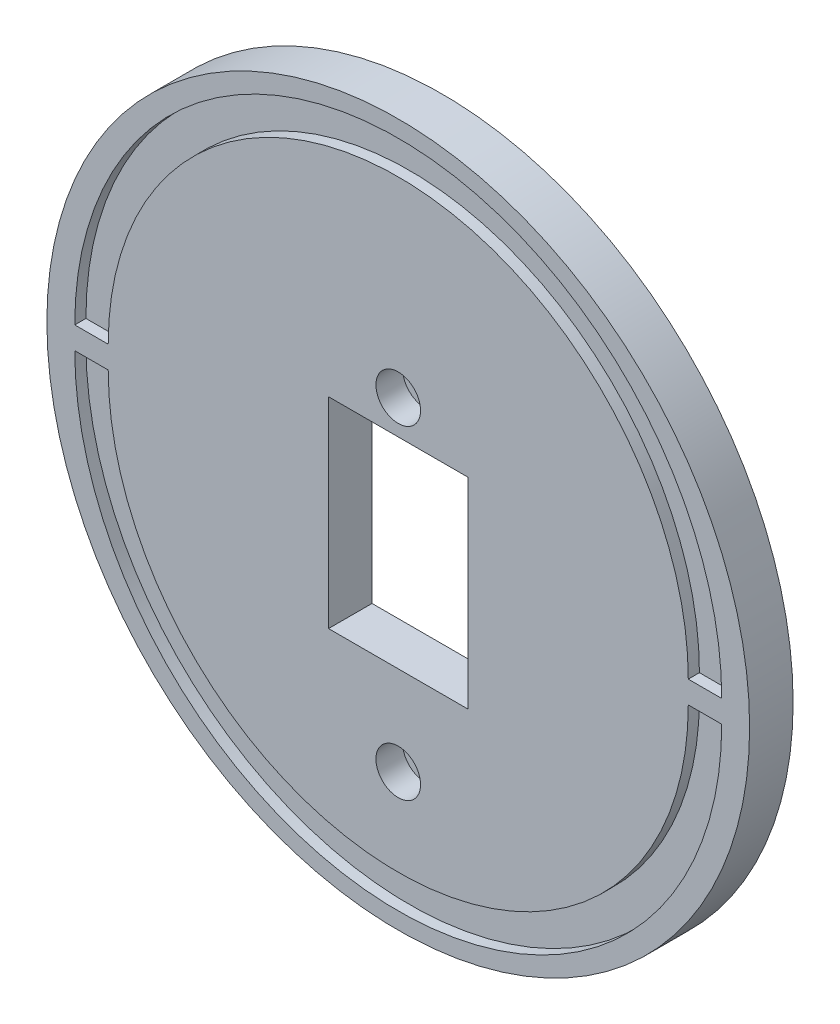
SolidWorks part; units mm, degrees
ref_plane "Alzado" through (0, 0, 0) normal (0, 0, 1) x (1, 0, 0)
ref_plane "Planta" through (0, 0, 0) normal (0, 1, 0) x (1, 0, 0)
ref_plane "Vista lateral" through (0, 0, 0) normal (1, 0, 0) x (0, 0, -1)
sketch "Croquis1" plane through (0, 0, 0) normal (0, 0, 1) x (1, 0, 0)
  circle A0 centre (-51.2357, 9.7866) radius 31.5
  dimension "D1" = 63
extrude "Saliente-Extruir1" add sketch "Croquis1" along normal blind 2.4
sketch "Croquis2" plane through (0, 0, 2.4) normal (0, 0, 1) x (1, 0, 0)
  line L0 (-51.2357, 9.7866) -> (-51.2357, -21.7134) construction
  line L1 (-51.2357, 9.7866) -> (-51.2357, 14.7866) construction
  line L2 (-51.2357, 14.7866) -> (-51.2357, 19.7866) construction
  line L3 (-51.2357, 19.7866) -> (-51.2357, 21.5866) construction
  line L4 (-51.2357, 21.5866) -> (-57.4857, 21.5866) construction
  line L6 (-57.4857, 21.5866) -> (-44.9857, 21.5866)
  line L7 (-57.4857, 21.5866) -> (-57.4857, -11.4134)
  line L8 (-57.4857, -11.4134) -> (-44.9857, -11.4134)
  line L9 (-44.9857, 21.5866) -> (-44.9857, -11.4134)
  line L14 (-59.2857, 23.3866) -> (-43.1857, 23.3866)
  line L15 (-59.2857, 23.3866) -> (-59.2857, -13.2134)
  line L16 (-59.2857, -13.2134) -> (-43.1857, -13.2134)
  line L17 (-43.1857, 23.3866) -> (-43.1857, -13.2134)
  circle A0 centre (-51.2357, 9.7866) radius 31.5 construction
  dimension "D2" = 5
  dimension "D3" = 1.8
  dimension "D4" = 6.25
  dimension "D5" = 12.5
  dimension "D6" = 33
  dimension "D7" = 1.8
  dimension "D8" = 1.8
  dimension "D9" = 1.8
  dimension "D10" = 1.8
  dimension "D11" = 8.5
extrude "Saliente-Extruir2" add sketch "Croquis2" along normal blind 22.5
sketch "Croquis5" plane through (0, 0, 2.4) normal (0, 0, 1) x (1, 0, 0)
  line L1 (-59.2857, 23.3866) -> (-43.1857, 23.3866)
  line L2 (-59.2857, 23.3866) -> (-59.2857, -13.2134)
  line L3 (-59.2857, -13.2134) -> (-43.1857, -13.2134)
  line L4 (-43.1857, 23.3866) -> (-43.1857, -13.2134)
extrude "Cortar-Extruir2" cut sketch "Croquis5" against normal blind 9
sketch "Croquis6" plane through (0, 0, 0) normal (0, 0, -1) x (-1, 0, 0)
  line L6 (51.2357, 9.7866) -> (73.5095, 32.0605) construction
  line L7 (73.5095, 32.0605) -> (73.5095, -12.4873) construction
  line L8 (73.5095, -12.4873) -> (28.9618, 32.0605) construction
  line L9 (28.9618, 32.0605) -> (28.9618, -12.4873) construction
  line L10 (28.9618, -12.4873) -> (51.2357, 9.7866) construction
  line L11 (51.2357, 23.3866) -> (53.2357, 23.3866)
  line L12 (43.1857, 23.3866) -> (59.2857, 23.3866) construction
  line L13 (53.2357, 23.3866) -> (53.2357, 43.3866)
  line L14 (53.2357, 43.3866) -> (49.2357, 43.3866)
  line L15 (49.2357, 43.3866) -> (49.2357, 23.3866)
  line L16 (49.2357, 23.3866) -> (51.2357, 23.3866)
  circle A0 centre (51.2357, 9.7866) radius 31.5 construction
  circle A1 centre (34.6187, 26.4036) radius 1.5
  circle A2 centre (67.8527, 26.4036) radius 1.5
  circle A3 centre (67.8527, -6.8304) radius 1.5
  circle A4 centre (34.6187, -6.8304) radius 1.5
  dimension "D3" = 8
  dimension "D1" = 20
  dimension "D2" = 4
extrude "Cortar-Extruir3" cut sketch "Croquis6" against normal blind 2.4
sketch "Croquis7" plane through (0, 21.5866, 0) normal (0, -1, 0) x (1, 0, 0)
  line L0 (-57.4857, 24.9) -> (-57.4857, 2.4) construction
  line L1 (-57.4857, 17.9) -> (-44.9857, 17.9)
  line L2 (-57.4857, 17.9) -> (-57.4857, 8.9)
  line L3 (-57.4857, 8.9) -> (-44.9857, 8.9)
  line L4 (-44.9857, 17.9) -> (-44.9857, 8.9)
  line L5 (-44.9857, 24.9) -> (-44.9857, 2.4) construction
  line L6 (-44.9857, 24.9) -> (-57.4857, 24.9) construction
  dimension "D1" = 9
  dimension "D2" = 7
extrude "Saliente-Extruir3" add sketch "Croquis7" along normal up to vertex (33 mm away)
sketch "Croquis8" plane through (0, 0, 17.9) normal (0, 0, 1) x (1, 0, 0)
  line L0 (-44.9857, -11.4134) -> (-44.9857, 21.5866) construction
  line L1 (-44.9857, -6.4134) -> (-57.4857, -6.4134)
  line L2 (-44.9857, -6.4134) -> (-44.9857, 16.5866)
  line L4 (-57.4857, -6.4134) -> (-57.4857, 16.5866)
  line L5 (-57.4857, -11.4134) -> (-57.4857, 21.5866) construction
  line L6 (-44.9857, -11.4134) -> (-57.4857, -11.4134) construction
  line L9 (-44.9857, 16.5866) -> (-49.2357, 16.5866)
  line L10 (-49.2357, 16.5866) -> (-49.2357, 18.5866)
  line L11 (-49.2357, 18.5866) -> (-53.2357, 18.5866)
  line L12 (-53.2357, 18.5866) -> (-53.2357, 16.5866)
  line L13 (-53.2357, 16.5866) -> (-57.4857, 16.5866)
  line L14 (-44.9857, 21.5866) -> (-57.4857, 21.5866) construction
  circle A0 centre (-51.2357, -9.4134) radius 1
  circle A1 centre (-51.2357, 19.6366) radius 1
  dimension "D3" = 2
  dimension "D6" = 1.95
  dimension "D1" = 5
  dimension "D2" = 5
  dimension "D4" = 4
  dimension "D5" = 2
  dimension "D7" = 2
extrude "Cortar-Extruir5" cut sketch "Croquis8" against normal blind 9
sketch "Croquis9" plane through (-44.9857, 0, 0) normal (-1, 0, 0) x (0, 0, 1)
  line L0 (8.9, -6.4134) -> (3.9, -11.4134)
  line L1 (8.9, -11.4134) -> (2.4, -11.4134) construction
  line L2 (3.9, -11.4134) -> (8.9, -11.4134)
  line L3 (8.9, -11.4134) -> (8.9, -6.4134)
  line L4 (8.9, 16.5866) -> (3.9, 21.5866)
  line L5 (8.9, 21.5866) -> (2.4, 21.5866) construction
  line L6 (3.9, 21.5866) -> (8.9, 21.5866)
  line L7 (8.9, 21.5866) -> (8.9, 16.5866)
extrude "Saliente-Extruir4" add sketch "Croquis9" along normal up to vertex (12.5 mm away)
sketch "Croquis10" plane through (0, 0, 8.9) normal (0, 0, 1) x (1, 0, 0)
  line L1 (-53.2357, 16.5866) -> (-49.2357, 16.5866)
  line L2 (-53.2357, 16.5866) -> (-53.2357, 18.5866)
  line L3 (-53.2357, 18.5866) -> (-49.2357, 18.5866)
  line L4 (-49.2357, 16.5866) -> (-49.2357, 18.5866)
extrude "Cortar-Extruir6" cut sketch "Croquis10" against normal blind 9
sketch "Croquis11" plane through (0, 0, 24.9) normal (0, 0, 1) x (1, 0, 0)
  line L0 (-57.4857, -11.4134) -> (-44.9857, -11.4134) construction
  line L1 (-57.4857, 16.5866) -> (-44.9857, 16.5866)
  line L2 (-57.4857, 16.5866) -> (-57.4857, -1.4134)
  line L3 (-57.4857, -1.4134) -> (-44.9857, -1.4134)
  line L4 (-44.9857, 16.5866) -> (-44.9857, -1.4134)
  line L5 (-44.9857, 21.5866) -> (-57.4857, 21.5866) construction
  line L6 (-43.1857, -13.2134) -> (-43.1857, 23.3866) construction
  line L7 (-59.2857, 23.3866) -> (-59.2857, -13.2134) construction
  circle A0 centre (-51.2357, 9.7866) radius 31.5
  dimension "D1" = 10
  dimension "D5" = 63
  dimension "D2" = 5
  dimension "D3" = 1.8
  dimension "D4" = 1.8
extrude "Saliente-Extruir5" add sketch "Croquis11" along normal blind 3.9
sketch "Croquis12" plane through (0, 0, 17.9) normal (0, 0, 1) x (1, 0, 0)
  circle A0 centre (-51.2357, 19.6366) radius 1
  circle A1 centre (-51.2357, -9.4134) radius 1
extrude "Cortar-Extruir7" cut sketch "Croquis12" along normal up to vertex
sketch "Croquis13" plane through (0, 0, 28.8) normal (0, 0, 1) x (1, 0, 0)
  circle A0 centre (-51.2357, 19.6366) radius 2
  circle A2 centre (-51.2357, -9.4134) radius 2
extrude "Cortar-Extruir8" cut sketch "Croquis13" against normal blind 2.4
sketch "Croquis14" plane through (0, 0, 0) normal (0, 0, -1) x (-1, 0, 0)
  circle A0 centre (51.2357, 9.7866) radius 31.5
extrude "Cortar-Extruir9" cut sketch "Croquis14" against normal up to vertex (24.9 mm away)
sketch "Croquis15" plane through (0, 0, 28.8) normal (0, 0, 1) x (1, 0, 0)
  line L1 (-44.9857, -1.4134) -> (-57.4857, -1.4134)
  line L2 (-44.9857, -1.4134) -> (-44.9857, 16.5866)
  line L3 (-44.9857, 16.5866) -> (-57.4857, 16.5866)
  line L4 (-57.4857, -1.4134) -> (-57.4857, 16.5866)
  circle A0 centre (-51.2357, 9.7866) radius 31.5
  circle A2 centre (-51.2357, 19.6366) radius 2
  circle A3 centre (-51.2357, -9.4134) radius 2
extrude "Saliente-Extruir6" add sketch "Croquis15" along normal blind 1
sketch "Croquis16" plane through (0, 0, 29.8) normal (0, 0, 1) x (1, 0, 0)
  line L0 (-19.7357, 9.7866) -> (-22.2357, 9.7866) construction
  line L1 (-22.2357, 9.7866) -> (-22.2357, 8.7866) construction
  line L2 (-22.2357, 8.7866) -> (-25.2357, 8.7866)
  line L3 (-51.2357, -1.4134) -> (-51.2357, 16.5866) construction
  line L4 (-57.4857, -1.4134) -> (-44.9857, -1.4134) construction
  line L5 (-44.9857, 16.5866) -> (-57.4857, 16.5866) construction
  line L6 (-22.2357, 9.7866) -> (-22.2357, 10.7866) construction
  line L7 (-22.2357, 10.7866) -> (-25.2357, 10.7866)
  line L8 (-80.2357, 9.7866) -> (-80.2357, 10.7866) construction
  line L9 (-80.2357, 9.7866) -> (-80.2357, 8.7866) construction
  line L10 (-82.7357, 9.7866) -> (-80.2357, 9.7866) construction
  line L11 (-80.2357, 10.7866) -> (-77.2357, 10.7866)
  line L12 (-80.2357, 8.7866) -> (-77.2357, 8.7866)
  circle A0 centre (-51.2357, 9.7866) radius 31.5 construction
  arc A1 (-25.2357, 8.7866) -> (-77.2357, 8.7866) centre (-51.2357, 8.7866) cw
  arc A2 (-22.2357, 8.7866) -> (-80.2357, 8.7866) centre (-51.2357, 8.7866) cw
  arc A3 (-22.2357, 10.7866) -> (-80.2357, 10.7866) centre (-51.2357, 10.7866) ccw
  arc A4 (-25.2357, 10.7866) -> (-77.2357, 10.7866) centre (-51.2357, 10.7866) ccw
  dimension "D1" = 2.5
  dimension "D2" = 1
  dimension "D3" = 3
  dimension "D4" = 3
extrude "Cortar-Extruir10" cut sketch "Croquis16" against normal blind 2
sketch "Croquis17" plane through (0, 0, 29.8) normal (0, 0, 1) x (1, 0, 0)
  circle A0 centre (-51.2357, 9.7866) radius 31.5
extrude "Cortar-Extruir11" cut sketch "Croquis17" against normal blind 1
